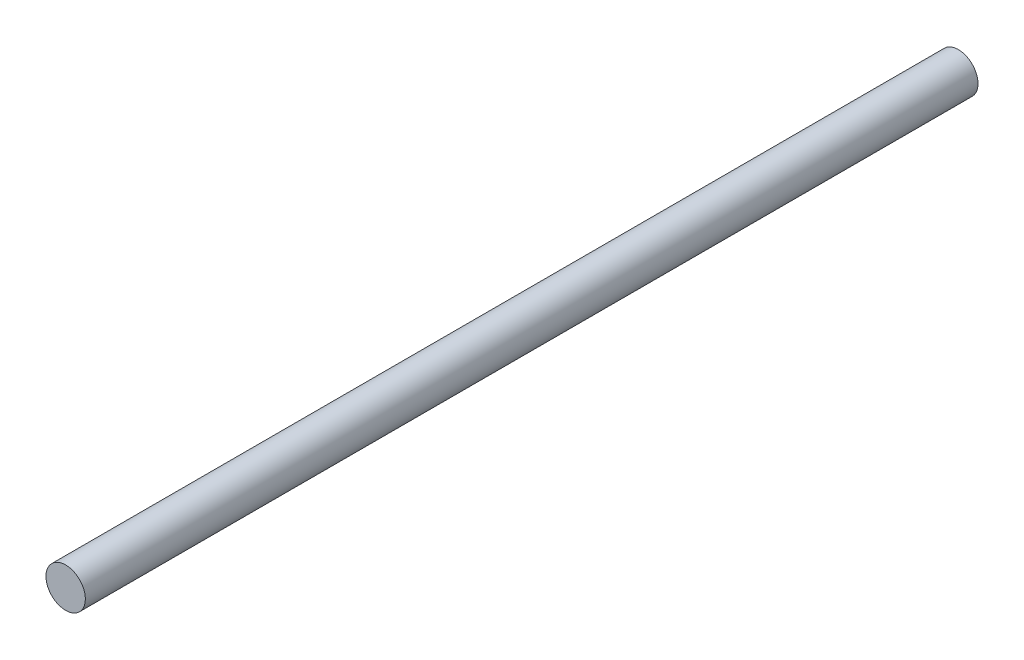
SolidWorks part; units mm, degrees
ref_plane "Alzado" through (0, 0, 0) normal (0, 0, 1) x (1, 0, 0)
ref_plane "Planta" through (0, 0, 0) normal (0, 1, 0) x (1, 0, 0)
ref_plane "Vista lateral" through (0, 0, 0) normal (1, 0, 0) x (0, 0, -1)
sketch "Croquis1" plane through (0, 0, 0) normal (0, 0, 1) x (1, 0, 0)
  circle A0 centre (0, 0) radius 1.5
  dimension "D1" = 3
extrude "Saliente-Extruir1" add sketch "Croquis1" along normal blind 68
